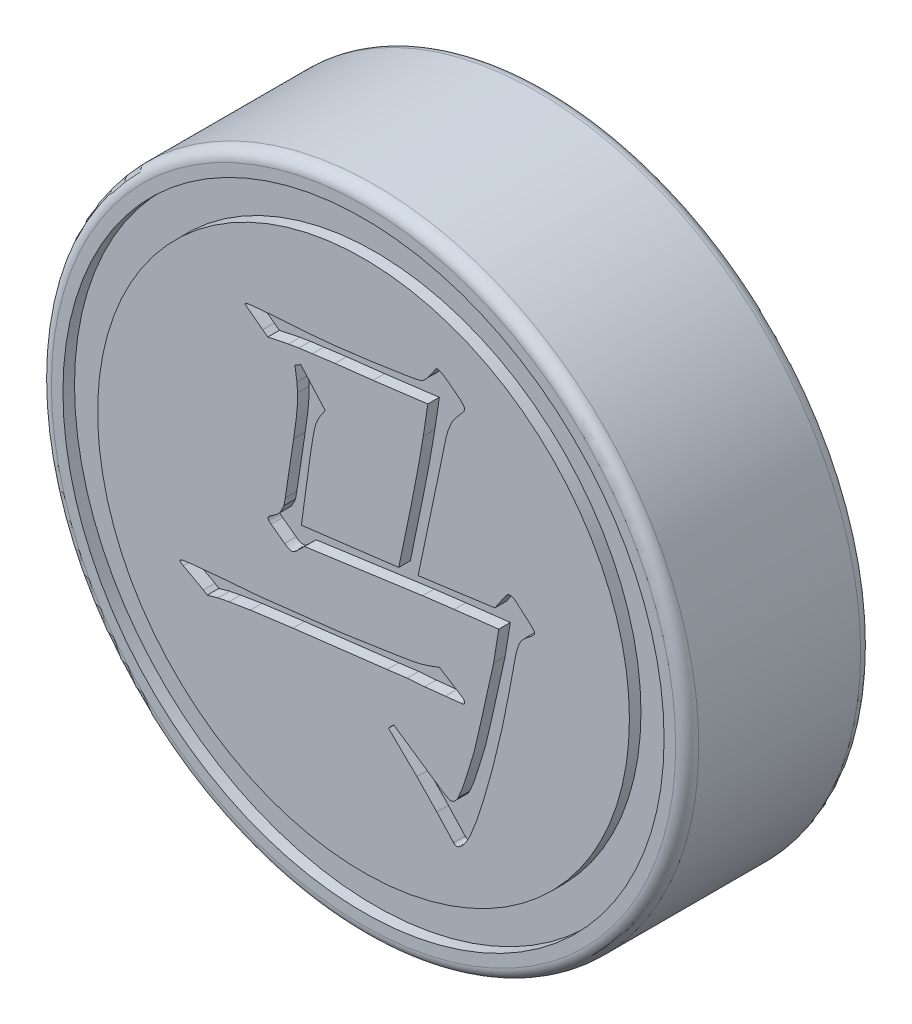
SolidWorks part; units mm, degrees
ref_plane "前视基准面" through (0, 0, 0) normal (0, 0, 1) x (1, 0, 0)
ref_plane "上视基准面" through (0, 0, 0) normal (0, 1, 0) x (1, 0, 0)
ref_plane "右视基准面" through (0, 0, 0) normal (1, 0, 0) x (0, 0, -1)
sketch "草图1" plane through (0, 0, 0) normal (0, 0, 1) x (1, 0, 0)
  circle A0 centre (0, 0) radius 14
extrude "凸台-拉伸1" add sketch "草图1" along normal blind 8
sketch "草图2" plane through (0, 0, 8) normal (0, 0, 1) x (1, 0, 0)
  circle A0 centre (0, 0) radius 13
  circle A1 centre (0, 0) radius 11.5
extrude "切除-拉伸1" cut sketch "草图2" against normal blind 0.5
sketch "草图3" plane through (0, 0, 0) normal (0, 0, -1) x (-1, 0, 0)
  circle A0 centre (0, 0) radius 5.1
extrude "切除-拉伸2" cut sketch "草图3" against normal blind 5
chamfer "倒角1" distance 0.5 angle 45 1 edges at (-5.1, 0, 0)
fillet "圆角1" radius 0.5 2 edges at (14, 0, 8) (14, 0, 0)
sketch "草图4" plane through (0, 0, 8) normal (0, 0, 1) x (1, 0, 0)
  text T0 "马" font "汉仪长仿宋体" height 13
extrude "切除-拉伸3" cut sketch "草图4" against normal blind 0.5
